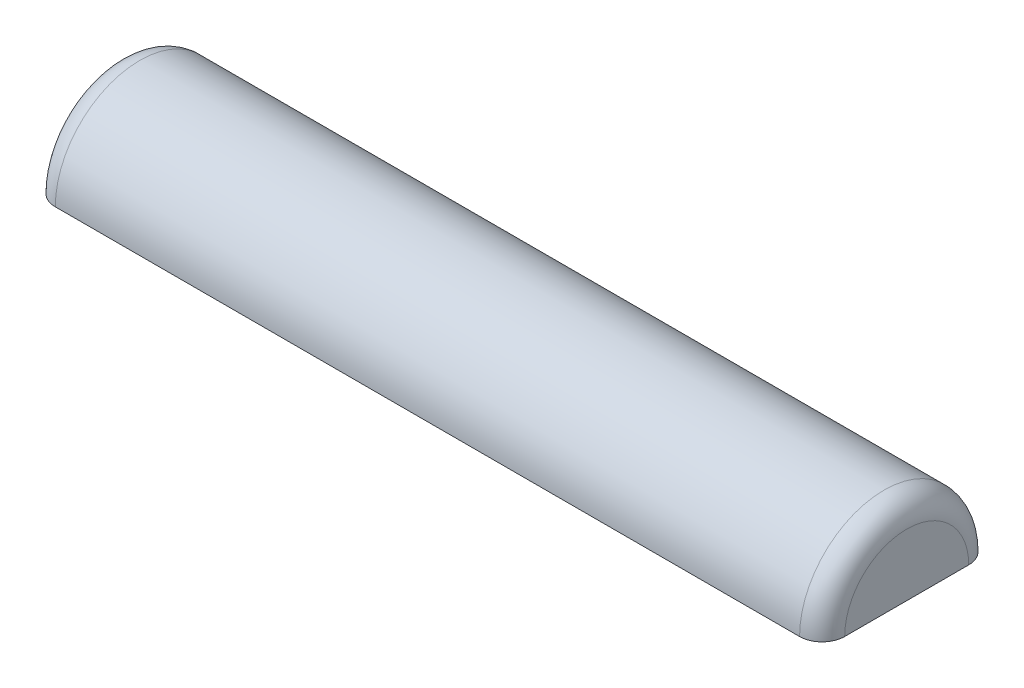
SolidWorks part; units mm, degrees
ref_plane "Front Plane" through (0, 0, 0) normal (0, 0, 1) x (1, 0, 0)
ref_plane "Top Plane" through (0, 0, 0) normal (0, 1, 0) x (1, 0, 0)
ref_plane "Right Plane" through (0, 0, 0) normal (1, 0, 0) x (0, 0, -1)
sketch "Sketch1" plane through (0, 0, 0) normal (1, 0, 0) x (0, 0, -1)
  line L0 (0, 0) -> (0.15, 0)
  arc A0 (0, 0) -> (0.15, 0) centre (0.075, 0) cw
  dimension "D1" = 0.15
extrude "Boss-Extrude1" add sketch "Sketch1" along normal blind 0.7
fillet "Fillet1" radius 0.02 2 edges at (0.7, 0.075, -0.075) (0, 0.075, -0.075)
